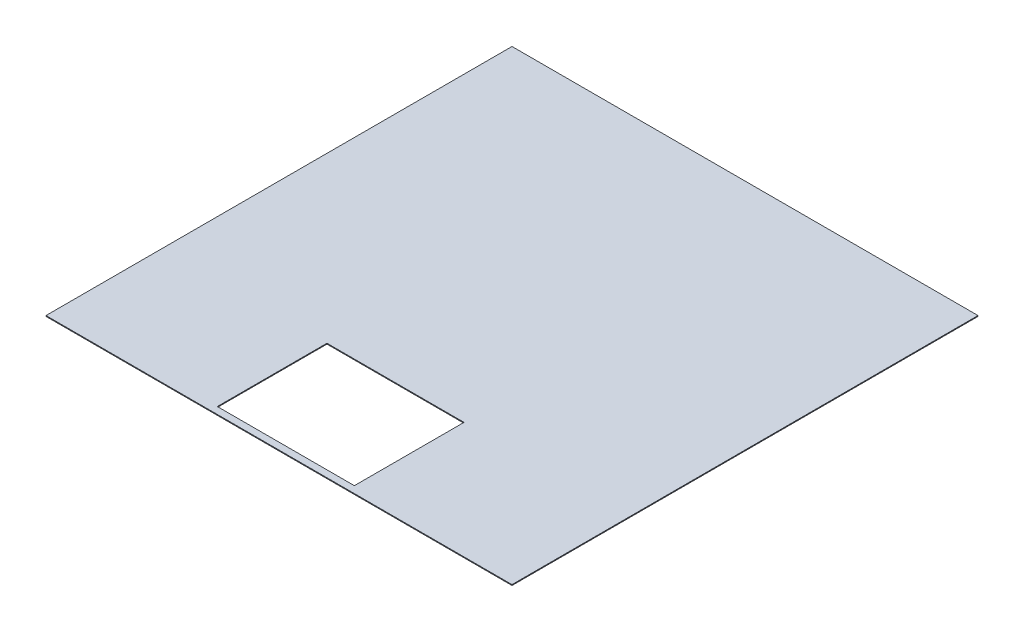
SolidWorks part; units mm, degrees
ref_plane "前视基准面" through (0, 0, 0) normal (0, 0, 1) x (1, 0, 0)
ref_plane "上视基准面" through (0, 0, 0) normal (0, 1, 0) x (1, 0, 0)
ref_plane "右视基准面" through (0, 0, 0) normal (1, 0, 0) x (0, 0, -1)
sketch "草图1" plane through (0, 0, 0) normal (0, 1, 0) x (1, 0, 0)
  line L0 (0, 0) -> (340, 0)
  line L1 (340, 0) -> (340, -340)
  line L2 (340, -340) -> (0, -340)
  line L3 (0, -340) -> (0, 0)
  line L4 (0, -260) -> (120, -340) construction
  line L5 (340, -260) -> (220, -340) construction
  line L6 (170, 0) -> (170, -340) construction
  line L7 (120, -340) -> (220, -340) construction
  line L8 (120, -335) -> (120, -255)
  line L9 (120, -255) -> (220, -255)
  line L10 (220, -255) -> (220, -335)
  line L11 (220, -335) -> (120, -335)
  point P12 (170, -340)
  dimension "D1" = 340
  dimension "D2" = 340
  dimension "D3" = 80
  dimension "D4" = 100
  dimension "D5" = 5
  dimension "D6" = 80
extrude "凸台-拉伸1" add sketch "草图1" along normal blind 0.6
